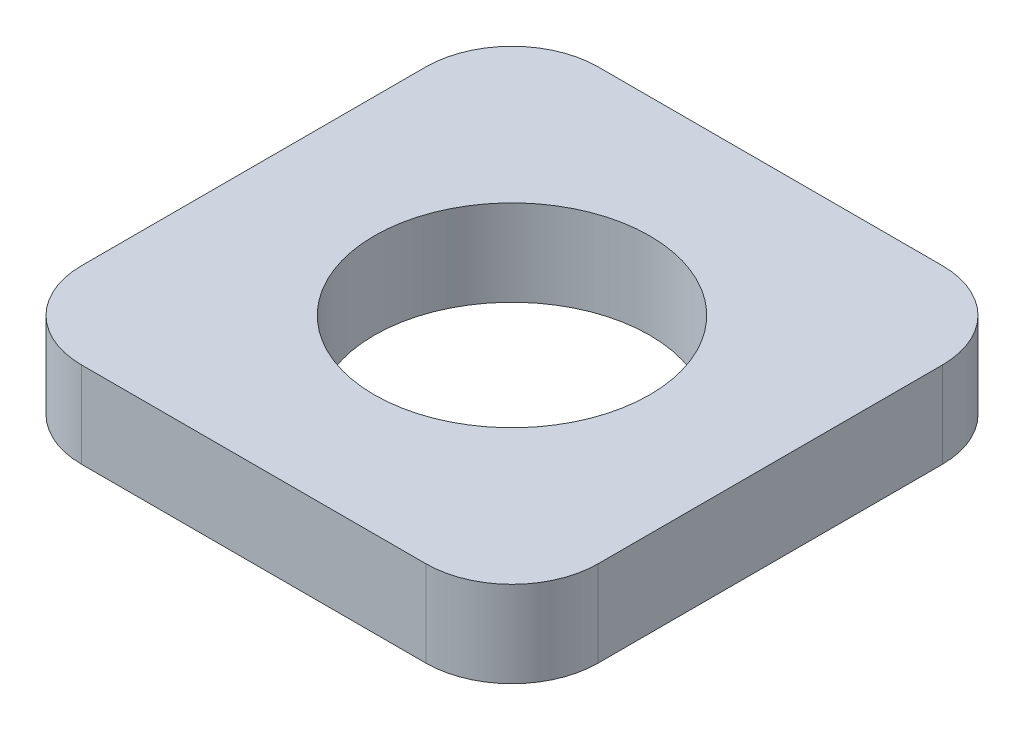
SolidWorks part; units mm, degrees
ref_plane "Plano frontal" through (0, 0, 0) normal (0, 0, 1) x (1, 0, 0)
ref_plane "Plano superior" through (0, 0, 0) normal (0, 1, 0) x (1, 0, 0)
ref_plane "Plano direito" through (0, 0, 0) normal (1, 0, 0) x (0, 0, -1)
sketch "Esboço1" plane through (0, 0, 0) normal (0, 1, 0) x (1, 0, 0)
  line L1 (-2, -3) -> (2, -3)
  line L2 (-3, -2) -> (-3, 2)
  line L3 (-2, 3) -> (2, 3)
  line L4 (3, -2) -> (3, 2)
  line L5 (-3, -3) -> (3, 3) construction
  line L6 (-3, 3) -> (3, -3) construction
  circle A0 centre (0, 0) radius 1.6
  arc A1 (3, 2) -> (2, 3) centre (2, 2) ccw
  arc A2 (3, -2) -> (2, -3) centre (2, -2) cw
  arc A3 (-2, -3) -> (-3, -2) centre (-2, -2) cw
  arc A4 (-2, 3) -> (-3, 2) centre (-2, 2) ccw
  point P0 (0, 0)
  dimension "D3" = 3.2
  dimension "D4" = 1
  dimension "D1" = 6
  dimension "D2" = 6
extrude "Ressalto-extrusão1" add sketch "Esboço1" along normal blind 1
